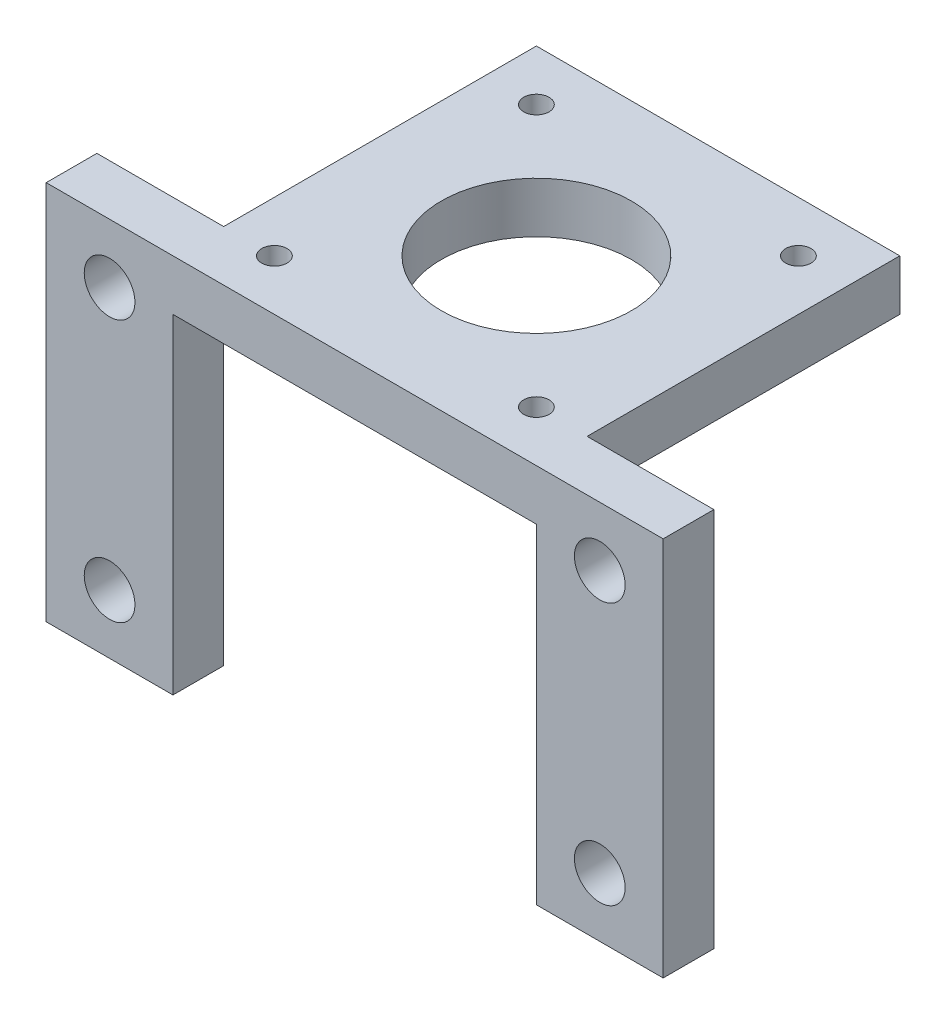
SolidWorks part; units mm, degrees
ref_plane "Alzado" through (0, 0, 0) normal (0, 0, 1) x (1, 0, 0)
ref_plane "Planta" through (0, 0, 0) normal (0, 1, 0) x (1, 0, 0)
ref_plane "Vista lateral" through (0, 0, 0) normal (1, 0, 0) x (0, 0, -1)
sketch "Croquis1" plane through (0, 0, 0) normal (0, 1, 0) x (1, 0, 0)
  line L1 (-21.5, -21.5) -> (21.5, -21.5)
  line L2 (-21.5, -21.5) -> (-21.5, 21.5)
  line L3 (-21.5, 21.5) -> (21.5, 21.5)
  line L4 (21.5, -21.5) -> (21.5, 21.5)
  line L5 (-21.5, -21.5) -> (21.5, 21.5) construction
  line L6 (-21.5, 21.5) -> (21.5, -21.5) construction
  circle A1 centre (-15.5, 15.5) radius 1.5
  circle A2 centre (15.5, 15.5) radius 1.5
  circle A3 centre (-15.5, -15.5) radius 1.5
  circle A4 centre (15.5, -15.5) radius 1.5
  circle A5 centre (0, 0) radius 11.25
  point P0 (0, 0)
  dimension "D5" = 3
  dimension "D6" = 3
  dimension "D9" = 3
  dimension "D11" = 3
  dimension "D13" = 22.5
  dimension "D1" = 43
  dimension "D2" = 43
  dimension "D3" = 6
  dimension "D4" = 6
  dimension "D7" = 6
  dimension "D8" = 6
  dimension "D10" = 6
  dimension "D12" = 6
extrude "Saliente-Extruir1" add sketch "Croquis1" along normal blind 6
sketch "Croquis2" plane through (0, 6, 0) normal (0, 1, 0) x (1, 0, 0)
  line L1 (-21.5, -21.5) -> (-36.5, -21.5)
  line L2 (-21.5, -21.5) -> (-21.5, -15.5)
  line L3 (-21.5, -15.5) -> (-36.5, -15.5)
  line L4 (-36.5, -21.5) -> (-36.5, -15.5)
  line L5 (21.5, -21.5) -> (36.5, -21.5)
  line L6 (21.5, -21.5) -> (21.5, -15.5)
  line L7 (21.5, -15.5) -> (36.5, -15.5)
  line L8 (36.5, -21.5) -> (36.5, -15.5)
  dimension "D1" = 15
  dimension "D2" = 6
  dimension "D3" = 15
  dimension "D4" = 6
extrude "Saliente-Extruir2" add sketch "Croquis2" against normal blind 45
sketch "Croquis3" plane through (0, 0, 15.5) normal (0, 0, -1) x (-1, 0, 0)
  line L0 (-21.5, -39) -> (-21.5, 0) construction
  line L2 (-36.5, -39) -> (-21.5, -39) construction
  line L3 (-36.5, 6) -> (-21.5, 6) construction
  line L4 (-36.5, -39) -> (-36.5, 6) construction
  line L5 (0, 23.65) -> (0, -23.65) construction
  circle A0 centre (-29, -32) radius 3
  circle A1 centre (-29, -1) radius 3
  circle A2 centre (29, -1) radius 3
  circle A3 centre (29, -32) radius 3
  dimension "D1" = 6
  dimension "D2" = 7.5
  dimension "D3" = 7
  dimension "D4" = 7
  dimension "D5" = 7.5
extrude "Cortar-Extruir1" cut sketch "Croquis3" against normal blind 45
